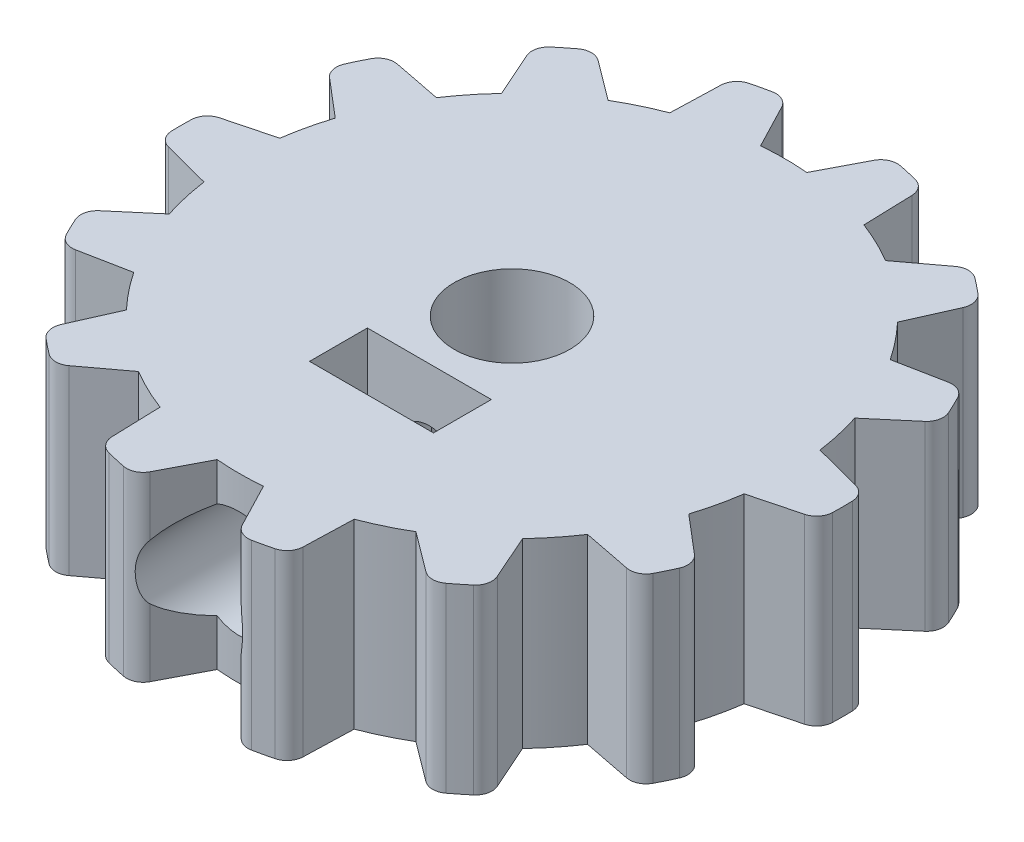
SolidWorks part; units mm, degrees
ref_plane "Front Plane" through (0, 0, 0) normal (0, 0, 1) x (1, 0, 0)
ref_plane "Top Plane" through (0, 0, 0) normal (0, 1, 0) x (1, 0, 0)
ref_plane "Right Plane" through (0, 0, 0) normal (1, 0, 0) x (0, 0, -1)
sketch "Sketch1" plane through (0, 0, 0) normal (0, 1, 0) x (1, 0, 0)
  circle A0 centre (0, 0) radius 20
  dimension "D1" = 40
extrude "Boss-Extrude1" add sketch "Sketch1" along normal blind 11
sketch "Sketch2" plane through (0, 11, 0) normal (0, 1, 0) x (1, 0, 0)
  line L0 (-3.125, 19.7544) -> (-1.3999, 16.4405)
  line L2 (1.3999, 16.4405) -> (3.125, 19.7544)
  circle A0 centre (0, 0) radius 20 construction
  arc A1 (-1.3999, 16.4405) -> (1.3999, 16.4405) centre (0, 0) cw
  arc A2 (3.125, 19.7544) -> (-3.125, 19.7544) centre (0, 0) ccw
  point P6 (0, 16.5)
  dimension "D1" = 16.5
  dimension "D2" = 55
  dimension "D3" = 6.25
extrude "Cut-Extrude1" cut sketch "Sketch2" against normal up to next
fillet "Fillet1" radius 1 2 edges at (3.125, 5.5, -19.7544) (-3.125, 5.5, -19.7544)
pattern_circular "CirPattern1" count 14 over 360 about axis through (0, 0, 0) along (0, 1, 0) of "Cut-Extrude1", "Fillet1"
sketch "Sketch3" plane through (0, 11, 0) normal (0, 1, 0) x (1, 0, 0)
  circle A0 centre (0, 0) radius 3.5
  point P1 (0, 3.5)
  point P5 (0, 0)
  dimension "D1" = 3.5
extrude "Cut-Extrude2" cut sketch "Sketch3" against normal up to next
sketch "Sketch4" plane through (0, 11, 0) normal (0, 1, 0) x (1, 0, 0)
  line L1 (-3.75, -5) -> (3.75, -5)
  line L2 (-3.75, -5) -> (-3.75, -8.5)
  line L3 (-3.75, -8.5) -> (3.75, -8.5)
  line L4 (3.75, -5) -> (3.75, -8.5)
  point P4 (0, -5)
  dimension "D1" = 5
  dimension "D2" = 3.5
  dimension "D3" = 7.5
extrude "Cut-Extrude3" cut sketch "Sketch4" against normal blind 9
sketch "Sketch6" plane through (0, 0, 0) normal (1, 0, 0) x (0, 0, -1)
  line L0 (0, 5.75) -> (-29.7973, 5.75) construction
  line L1 (-8.5, 2) -> (-5, 2) construction
  line L2 (0, 5.75) -> (0, 7.75)
  line L3 (0, 7.75) -> (-10, 7.75)
  line L4 (-10, 7.75) -> (-10, 9)
  line L5 (-10, 9) -> (-25, 9)
  line L6 (-25, 9) -> (-25, 5.75)
  line L7 (-25, 5.75) -> (0, 5.75)
  dimension "D1" = 3.75
  dimension "D2" = 4
  dimension "D3" = 6.5
  dimension "D4" = 10
  dimension "D5" = 25
revolve "Cut-Revolve1" cut sketch "Sketch6" angle 360 about L0
